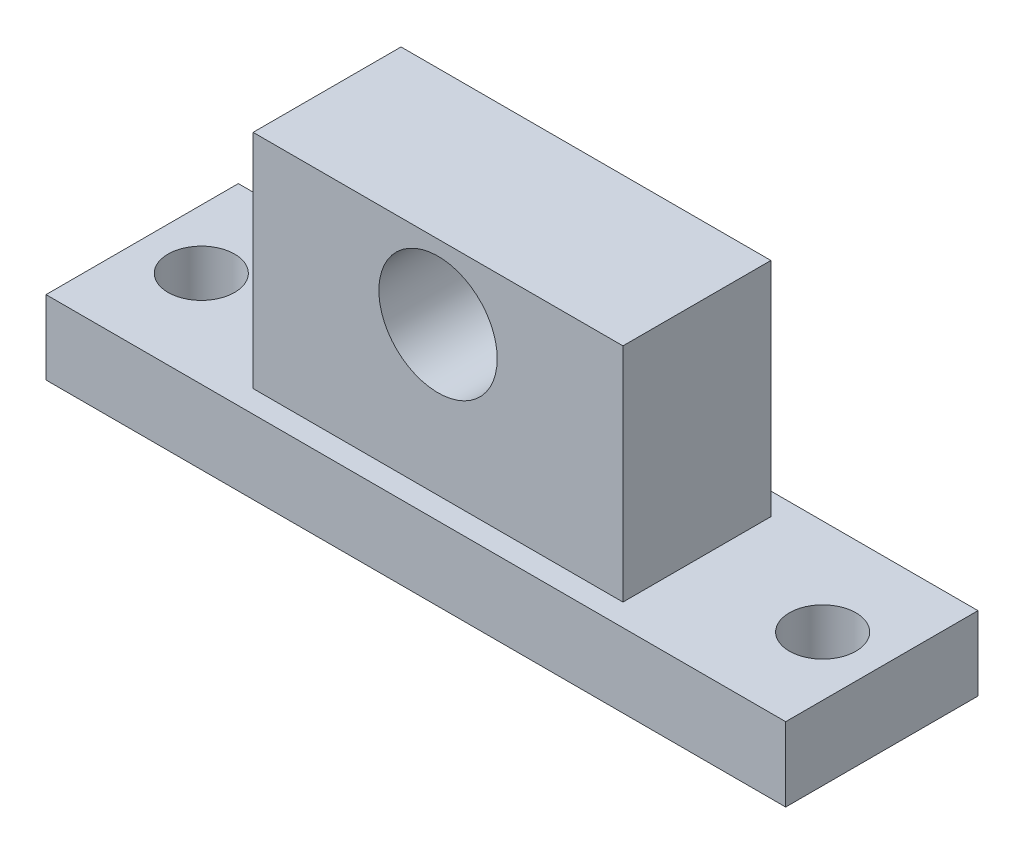
SolidWorks part; units mm, degrees
material "6061 Alloy"
ref_plane "Front Plane" through (0, 0, 0) normal (0, 0, 1) x (1, 0, 0)
ref_plane "Top Plane" through (0, 0, 0) normal (0, 1, 0) x (1, 0, 0)
ref_plane "Right Plane" through (0, 0, 0) normal (1, 0, 0) x (0, 0, -1)
sketch "Sketch1" plane through (0, 0, 0) normal (0, 1, 0) x (1, 0, 0)
  line L1 (-25, -6.5) -> (25, -6.5)
  line L2 (-25, -6.5) -> (-25, 6.5)
  line L3 (-25, 6.5) -> (25, 6.5)
  line L4 (25, -6.5) -> (25, 6.5)
  line L5 (-25, -6.5) -> (25, 6.5) construction
  line L6 (-25, 6.5) -> (25, -6.5) construction
  point P0 (0, 0)
  dimension "D1" = 13
  dimension "D2" = 50
extrude "Boss-Extrude1" add sketch "Sketch1" along normal blind 5
sketch "Sketch2" plane through (0, 5, 0) normal (0, 1, 0) x (1, 0, 0)
  line L1 (-25, 6.5) -> (-25, -6.5) construction
  circle A0 centre (-21, 0) radius 2.25
  circle A1 centre (21, 0) radius 2.25
  dimension "D1" = 4.5
  dimension "D2" = 4.5
  dimension "D3" = 42
  dimension "D4" = 4
extrude "Cut-Extrude1" cut sketch "Sketch2" against normal blind 5
sketch "Sketch3" plane through (0, 5, 0) normal (0, 1, 0) x (1, 0, 0)
  line L1 (-12.5, -5) -> (12.5, -5)
  line L2 (-12.5, -5) -> (-12.5, 5)
  line L3 (-12.5, 5) -> (12.5, 5)
  line L4 (12.5, -5) -> (12.5, 5)
  line L5 (-12.5, -5) -> (12.5, 5) construction
  line L6 (-12.5, 5) -> (12.5, -5) construction
  point P0 (0, 0)
  dimension "D1" = 10
  dimension "D2" = 25
extrude "Boss-Extrude2" add sketch "Sketch3" along normal blind 15
sketch "Sketch4" plane through (0, 0, 5) normal (0, 0, 1) x (1, 0, 0)
  line L1 (-25, 0) -> (25, 0) construction
  circle A0 centre (0, 15) radius 4
  dimension "D1" = 8
  dimension "D2" = 15
extrude "Cut-Extrude2" cut sketch "Sketch4" against normal blind 15
